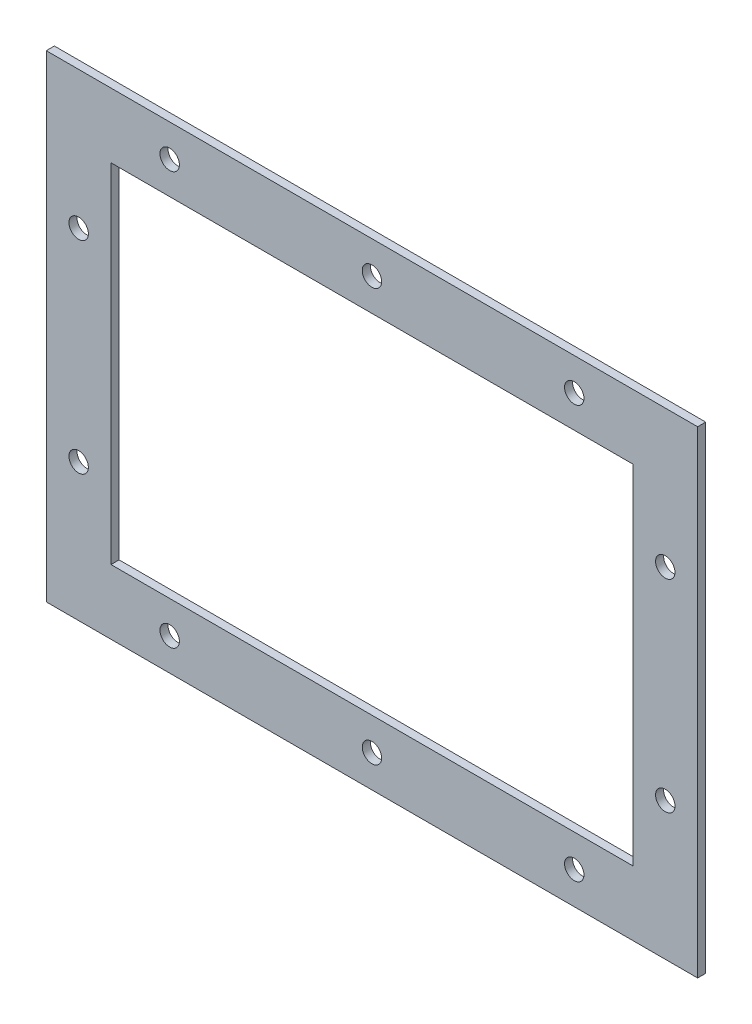
SolidWorks part; units mm, degrees
material "ASTM A36 Steel"
ref_plane "Front Plane" through (0, 0, 0) normal (0, 0, 1) x (1, 0, 0)
ref_plane "Top Plane" through (0, 0, 0) normal (0, 1, 0) x (1, 0, 0)
ref_plane "Right Plane" through (0, 0, 0) normal (1, 0, 0) x (0, 0, -1)
sketch "Sketch1" plane through (0, 0, 0) normal (0, 0, 1) x (1, 0, 0)
  line L0 (168.7801, -140.5) -> (168.7801, 154.5)
  line L1 (-193.7199, -100.5) -> (128.7801, -100.5)
  line L2 (-193.7199, -100.5) -> (-193.7199, 114.5)
  line L3 (-193.7199, 114.5) -> (128.7801, 114.5)
  line L4 (128.7801, -100.5) -> (128.7801, 114.5)
  line L5 (-193.7199, -100.5) -> (128.7801, 114.5) construction
  line L6 (-193.7199, 114.5) -> (128.7801, -100.5) construction
  line L7 (-233.7199, 154.5) -> (168.7801, 154.5)
  line L8 (-233.7199, -140.5) -> (-233.7199, 154.5)
  line L9 (-233.7199, -140.5) -> (168.7801, -140.5)
  point P0 (-32.4699, 7)
  dimension "D1" = 215
  dimension "D2" = 322.5
  dimension "D3" = 40
extrude "Boss-Extrude1" add sketch "Sketch1" along normal blind 5
sketch "Sketch2" plane through (0, 0, 5) normal (0, 0, 1) x (1, 0, 0)
  line L0 (-233.7199, 154.5) -> (-233.7199, -140.5) construction
  line L1 (-233.7199, -140.5) -> (168.7801, -140.5) construction
  line L3 (168.7801, -140.5) -> (168.7801, 154.5) construction
  line L4 (-233.7199, -140.5) -> (168.7801, -140.5) construction
  circle A0 centre (-213.7199, 69.5) radius 6
  circle A1 centre (-213.7199, -55.5) radius 6
  circle A5 centre (-157.4699, -120.5) radius 6
  circle A6 centre (-32.4699, -120.5) radius 6
  circle A7 centre (92.5301, -120.5) radius 6
  circle A12 centre (92.5301, 134.5) radius 6
  circle A13 centre (-32.4699, 134.5) radius 6
  circle A14 centre (-157.4699, 134.5) radius 6
  circle A15 centre (148.7801, -55.5) radius 6
  circle A16 centre (148.7801, 69.5) radius 6
  dimension "D1" = 125
  dimension "D2" = 12
  dimension "D3" = 12
  dimension "D4" = 20
  dimension "D5" = 85
  dimension "D8" = 20
  dimension "D14" = 125
  dimension "D15" = 125
  dimension "D13" = 76.25
extrude "Cut-Extrude1" cut sketch "Sketch2" against normal blind 5
